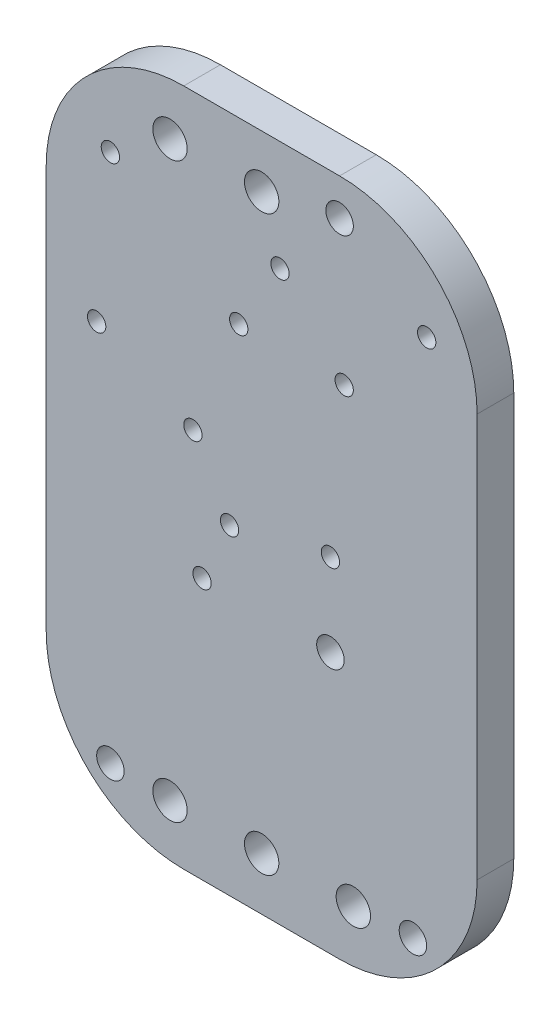
SolidWorks part; units mm, degrees
ref_plane "Front Plane" through (0, 0, 0) normal (0, 0, 1) x (1, 0, 0)
ref_plane "Top Plane" through (0, 0, 0) normal (0, 1, 0) x (1, 0, 0)
ref_plane "Right Plane" through (0, 0, 0) normal (1, 0, 0) x (0, 0, -1)
sketch "Sketch1" plane through (0, 0, 0) normal (0, 0, 1) x (1, 0, 0)
  line L0 (0.3, 11.9) -> (0.3, 3.1)
  line L1 (3.3, 0.1) -> (6.7, 0.1)
  line L2 (9.7, 3.1) -> (9.7, 11.9)
  line L3 (6.7, 14.9) -> (3.3, 14.9)
  arc A0 (0.3, 3.1) -> (3.3, 0.1) centre (3.3, 3.1) ccw
  arc A1 (6.7, 0.1) -> (9.7, 3.1) centre (6.7, 3.1) ccw
  arc A2 (9.7, 11.9) -> (6.7, 14.9) centre (6.7, 11.9) ccw
  arc A3 (3.3, 14.9) -> (0.3, 11.9) centre (3.3, 11.9) ccw
extrude "BOARD" add sketch "Sketch1" along normal blind 0.8 separate body
sketch "Sketch2" plane through (0, 0, 0) normal (0, 0, 1) x (1, 0, 0)
  circle A0 centre (1.7, 1.3) radius 0.3
  circle A1 centre (8.3, 1.3) radius 0.3
  circle A2 centre (6.7, 14.1) radius 0.3
  circle A3 centre (5, 13.75) radius 0.375
  circle A4 centre (3, 13.75) radius 0.375
  circle A5 centre (3, 1.25) radius 0.375
  circle A6 centre (5, 1.25) radius 0.375
  circle A7 centre (7, 1.25) radius 0.375
extrude "NON-PLATED HOLES" cut sketch "Sketch2" along normal through all
sketch "Sketch3" plane through (0, 0, 0) normal (0, 0, 1) x (1, 0, 0)
  circle A0 centre (4.5, 11) radius 0.2
  circle A1 centre (1.4, 9.5) radius 0.2
  circle A2 centre (8.6, 12.8) radius 0.2
  circle A3 centre (1.7, 12.85) radius 0.2
  circle A4 centre (3.5, 8.5) radius 0.2
  circle A5 centre (3.7, 5.8) radius 0.2
  circle A6 centre (6.8, 11) radius 0.2
  circle A7 centre (6.5, 7.6) radius 0.2
  circle A8 centre (6.5, 5.8) radius 0.3
  circle A9 centre (4.3, 7.1) radius 0.2
  circle A10 centre (5.4, 12.5) radius 0.2
extrude "PLATED HOLES" cut sketch "Sketch3" along normal through all
ref_plane "Plane1" through (0, 0, 100) normal (0, 0, 1) x (1, 0, 0)
